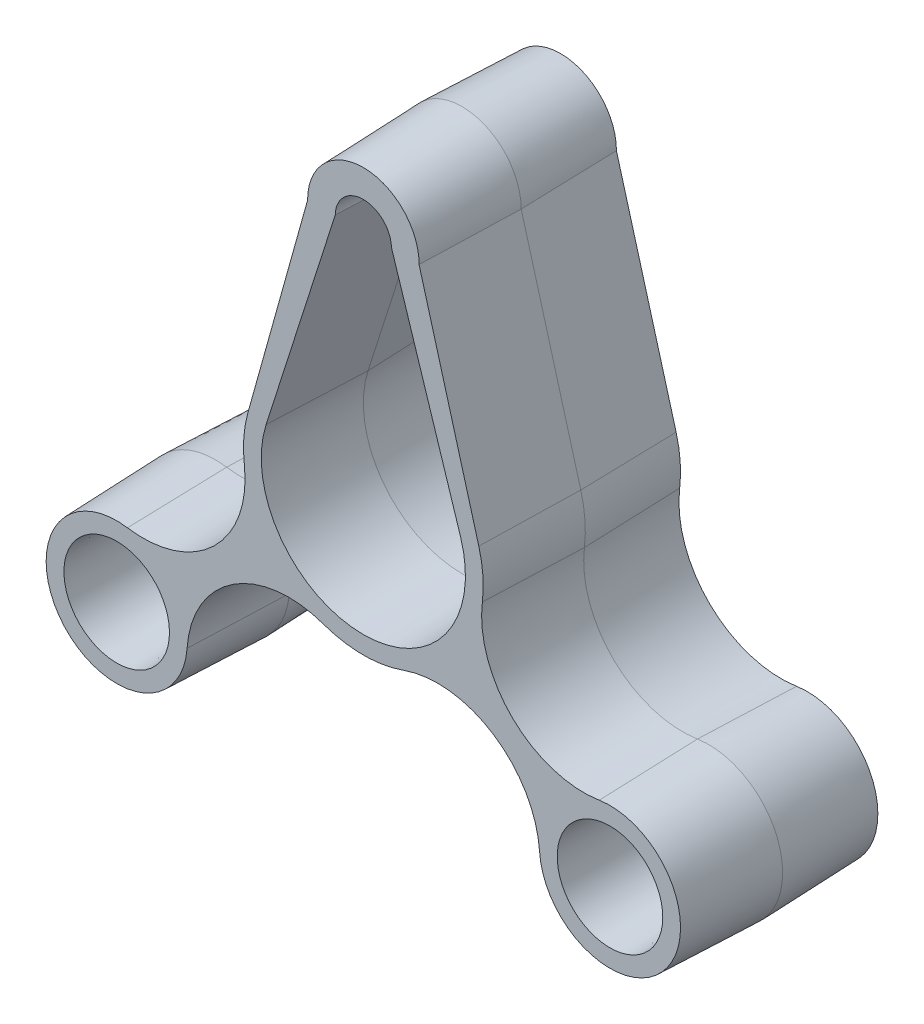
SolidWorks part; units mm, degrees
ref_plane "Front Plane" through (0, 0, 0) normal (0, 0, 1) x (1, 0, 0)
ref_plane "Top Plane" through (0, 0, 0) normal (0, 1, 0) x (1, 0, 0)
ref_plane "Right Plane" through (0, 0, 0) normal (1, 0, 0) x (0, 0, -1)
sketch "Sketch1" plane through (0, 0, 0) normal (0, 0, 1) x (1, 0, 0)
  line L0 (0, 0) -> (0, 50539.4986) construction
  line L1 (0, 0) -> (-50539.4986, 0) construction
  line L2 (-12, 50) -> (-24.0797, 6.7209)
  line L3 (12, 50) -> (24.0797, 6.7209)
  line L4 (-5, 50) -> (-19.0486, 6.0951)
  line L5 (5, 50) -> (19.0486, 6.0951)
  arc A0 (-8.379, -23.554) -> (8.379, -23.554) centre (0, 0) ccw
  arc A1 (-19.0486, 6.0951) -> (19.0486, 6.0951) centre (0, 0) ccw
  circle A2 centre (-50, -40) radius 10
  arc A3 (-47.7174, -25.1747) -> (-35.0352, -41.0274) centre (-50, -40) ccw
  arc A4 (47.7174, -25.1747) -> (35.0352, -41.0274) centre (50, -40) cw
  circle A5 centre (50, -40) radius 10
  arc A6 (-47.7174, -25.1747) -> (-24.8188, -3.0042) centre (-44.6739, -5.4076) ccw
  arc A7 (47.7174, -25.1747) -> (24.8188, -3.0042) centre (44.6739, -5.4076) cw
  arc A8 (-35.0352, -41.0274) -> (-8.379, -23.554) centre (-15.0822, -42.3973) cw
  arc A9 (35.0352, -41.0274) -> (8.379, -23.554) centre (15.0822, -42.3973) ccw
  arc A10 (47.7174, -25.1747) -> (24.8188, -3.0042) centre (44.6739, -5.4076) cw
  arc A11 (24.8188, -3.0042) -> (24.0797, 6.7209) centre (0, 0) ccw
  arc A12 (5, 50) -> (-5, 50) centre (0, 50) ccw
  arc A13 (12, 50) -> (-12, 50) centre (0, 50) ccw
  arc A14 (-24.0797, 6.7209) -> (-24.8188, -3.0042) centre (0, 0) ccw
  dimension "D1" = 50
  dimension "D3" = 20
  dimension "D4" = 30
  dimension "D5" = 40
  dimension "D6" = 50
  dimension "D8" = 20
  dimension "D9" = 20
  dimension "D10" = 20
  dimension "D11" = 20
  dimension "D12" = 15
  dimension "D13" = 20
  dimension "D14" = 10
  dimension "D15" = 24
  dimension "D2" = 50
  dimension "D7" = 100
  dimension "D16" = 50
  dimension "D17" = 40
  dimension "D18" = 0.4418
extrude "Boss-Extrude1" add sketch "Sketch1" along normal mid plane 40 draft 2 contours L2 A14 A6 A3 A8 A0 A9 A4 A7 A11 L3 A13 A5 A2 A12 L5 A1 L4
